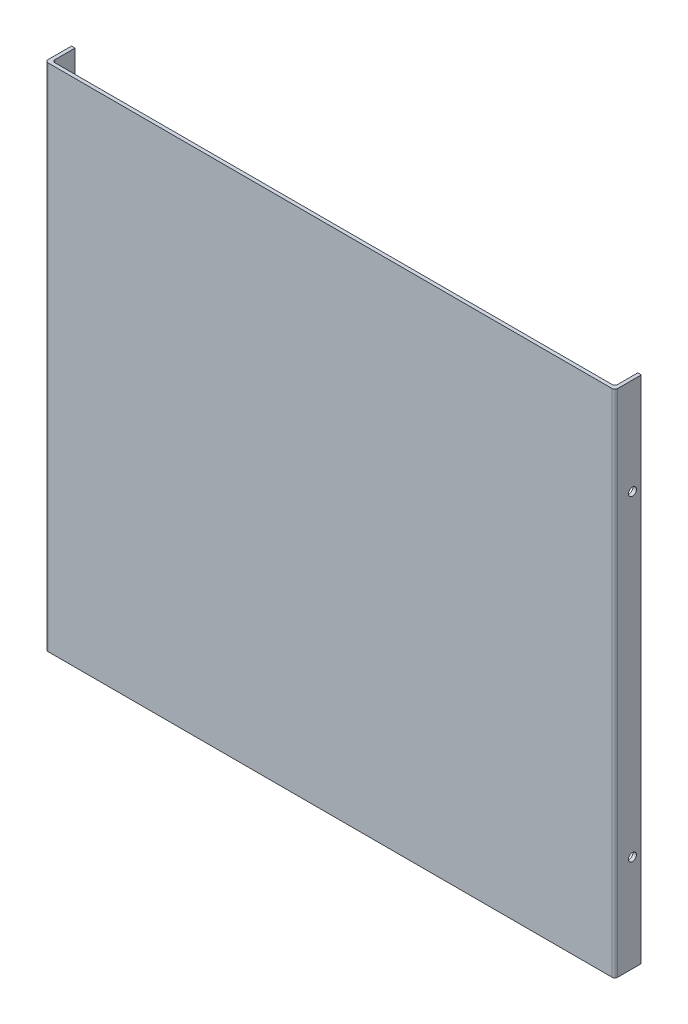
SolidWorks part; units mm, degrees
ref_plane "Plan de face" through (0, 0, 0) normal (0, 0, 1) x (1, 0, 0)
ref_plane "Plan de dessus" through (0, 0, 0) normal (0, 1, 0) x (1, 0, 0)
ref_plane "Plan de droite" through (0, 0, 0) normal (1, 0, 0) x (0, 0, -1)
sketch "Esquisse1" plane through (0, 0, 0) normal (0, 0, 1) x (1, 0, 0)
  line L1 (-160, -145) -> (160, -145)
  line L2 (-160, -145) -> (-160, 145)
  line L3 (-160, 145) -> (160, 145)
  line L4 (160, -145) -> (160, 145)
  line L5 (-160, -145) -> (160, 145) construction
  line L6 (-160, 145) -> (160, -145) construction
  point P0 (0, 0)
  dimension "D1" = 320
  dimension "D2" = 290
extrude "Boss.-Extru.1" add sketch "Esquisse1" along normal blind 2
sketch "Esquisse2" plane through (-160, 0, 0) normal (-1, 0, 0) x (0, 0, 1)
  line L0 (2, -145) -> (0, -145) construction
  line L1 (2, 145) -> (-13, 145)
  line L2 (2, 145) -> (2, -145)
  line L3 (2, -145) -> (-13, -145)
  line L4 (-13, 145) -> (-13, -145)
  dimension "D1" = 15
extrude "Boss.-Extru.2" add sketch "Esquisse2" along normal blind 2
fillet "Congé1" radius 1.5 2 edges at (-162, 0, 2)
mirror "Symétrie1" about plane through (0, 0, 0) normal (1, 0, 0) of "Congé1", "Boss.-Extru.2"
hole_wizard "Dégagement M41" positions "Esquisse4" profile "Esquisse3" hole size "M4" standard "Ansi Metric" end condition through all
sketch "Esquisse4" plane through (-162, 0, 0) normal (-1, 0, 0) x (0, 0, 1)
  line L2 (-13, 145) -> (-13, -145) construction
  line L3 (0.5, 0) -> (-31.0704, 0) construction
  line L4 (8.25, 0) -> (-8.25, 0) construction
  point P0 (-8, -90)
  point P29 (-8, 90)
  dimension "D1" = 90
  dimension "D2" = 5
sketch "Esquisse3" plane through (-162, -90, -8) normal (0, 1, 0) x (0, 0, 1)
  line L0 (0, 0) -> (0, 324)
  line L1 (0, 324) -> (2.25, 324)
  line L2 (2.25, 324) -> (2.25, 0)
  line L5 (2.25, 0) -> (0, 0)
  line L11 (0, -6.35) -> (0, 107.95) construction
  dimension "Diamètre du perçage jusqu'au prochain" = 4.5
  dimension "Profondeur du perçage jusqu'au prochain" = 324
